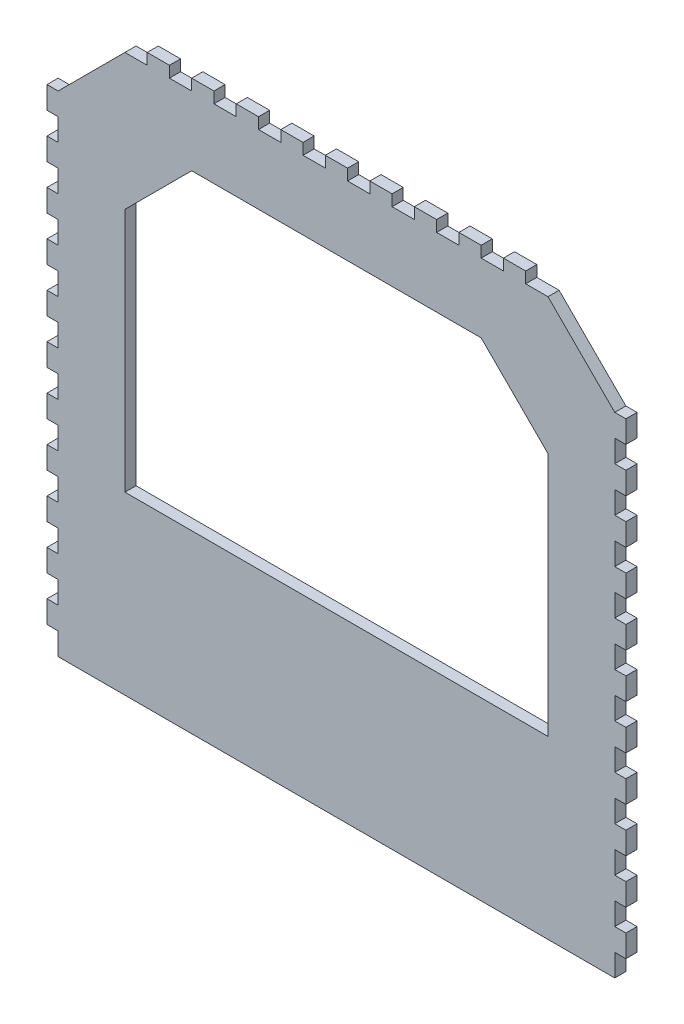
SolidWorks part; units mm, degrees
material "Buche"
ref_plane "Ebene vorne" through (0, 0, 0) normal (0, 0, 1) x (1, 0, 0)
ref_plane "Ebene oben" through (0, 0, 0) normal (0, 1, 0) x (1, 0, 0)
ref_plane "Ebene rechts" through (0, 0, 0) normal (1, 0, 0) x (0, 0, -1)
sketch "Skizze1" plane through (0, 0, 0) normal (0, 0, 1) x (1, 0, 0)
  line L0 (460.8962, 291.6639) -> (470.8962, 291.6639)
  line L1 (470.8962, 291.6639) -> (470.8962, 296.6639)
  line L2 (470.8962, 296.6639) -> (480.8962, 296.6639)
  line L3 (480.8962, 296.6639) -> (480.8962, 291.6639)
  line L4 (480.8962, 291.6639) -> (490.8962, 291.6639)
  line L5 (490.8962, 291.6639) -> (490.8962, 296.6639)
  line L6 (490.8962, 296.6639) -> (500.8962, 296.6639)
  line L7 (500.8962, 296.6639) -> (500.8962, 291.6639)
  line L8 (500.8962, 291.6639) -> (510.8962, 291.6639)
  line L9 (510.8962, 291.6639) -> (510.8962, 296.6639)
  line L10 (510.8962, 296.6639) -> (520.8962, 296.6639)
  line L11 (520.8962, 296.6639) -> (520.8962, 291.6639)
  line L12 (520.8962, 291.6639) -> (530.8962, 291.6639)
  line L13 (530.8962, 291.6639) -> (530.8962, 296.6639)
  line L14 (530.8962, 296.6639) -> (540.8962, 296.6639)
  line L15 (540.8962, 296.6639) -> (540.8962, 291.6639)
  line L16 (540.8962, 291.6639) -> (550.8962, 291.6639)
  line L17 (550.8962, 291.6639) -> (550.8962, 296.6639)
  line L18 (550.8962, 296.6639) -> (560.8962, 296.6639)
  line L19 (560.8962, 296.6639) -> (560.8962, 291.6639)
  line L20 (560.8962, 291.6639) -> (570.8962, 291.6639)
  line L21 (570.8962, 291.6639) -> (570.8962, 296.6639)
  line L22 (570.8962, 296.6639) -> (580.8962, 296.6639)
  line L23 (580.8962, 296.6639) -> (580.8962, 291.6639)
  line L24 (580.8962, 291.6639) -> (590.8962, 291.6639)
  line L25 (590.8962, 291.6639) -> (590.8962, 296.6639)
  line L26 (590.8962, 296.6639) -> (600.8962, 296.6639)
  line L27 (600.8962, 296.6639) -> (600.8962, 291.6639)
  line L28 (600.8962, 291.6639) -> (610.8962, 291.6639)
  line L29 (610.8962, 291.6639) -> (610.8962, 296.6639)
  line L30 (610.8962, 296.6639) -> (620.8962, 296.6639)
  line L31 (620.8962, 296.6639) -> (620.8962, 291.6639)
  line L32 (620.8962, 291.6639) -> (630.8962, 291.6639)
  line L33 (630.8962, 291.6639) -> (630.8962, 296.6639)
  line L34 (630.8962, 296.6639) -> (640.8962, 296.6639)
  line L35 (640.8962, 296.6639) -> (640.8962, 291.6639)
  line L36 (640.8962, 291.6639) -> (650.8962, 291.6639)
  line L197 (680.8962, 261.6639) -> (685.8962, 261.6639)
  line L198 (685.8962, 261.6639) -> (685.8962, 251.6639)
  line L199 (430.8962, 231.6639) -> (430.8962, 221.6639)
  line L200 (490.8962, 260.635) -> (620.8962, 260.635)
  line L201 (680.8962, 251.6639) -> (680.8962, 241.6639)
  line L202 (680.8962, 241.6639) -> (685.8962, 241.6639)
  line L203 (685.8962, 241.6639) -> (685.8962, 231.6639)
  line L204 (430.8962, 241.6639) -> (425.8962, 241.6639)
  line L205 (430.8962, 251.6639) -> (430.8962, 241.6639)
  line L206 (425.8962, 231.6639) -> (430.8962, 231.6639)
  line L207 (460.8962, 120.635) -> (460.8962, 230.635)
  line L208 (680.8962, 231.6639) -> (680.8962, 221.6639)
  line L209 (685.8962, 231.6639) -> (680.8962, 231.6639)
  line L210 (425.8962, 241.6639) -> (425.8962, 231.6639)
  line L211 (430.8962, 211.6639) -> (430.8962, 201.6639)
  line L212 (430.8962, 221.6639) -> (425.8962, 221.6639)
  line L213 (425.8962, 211.6639) -> (430.8962, 211.6639)
  line L214 (430.8962, 261.6639) -> (460.8962, 291.6639)
  line L215 (680.8962, 221.6639) -> (685.8962, 221.6639)
  line L216 (685.8962, 221.6639) -> (685.8962, 211.6639)
  line L217 (680.8962, 211.6639) -> (680.8962, 201.6639)
  line L218 (425.8962, 221.6639) -> (425.8962, 211.6639)
  line L219 (430.8962, 261.6639) -> (425.8962, 261.6639)
  line L220 (685.8962, 211.6639) -> (680.8962, 211.6639)
  line L221 (680.8962, 201.6639) -> (685.8962, 201.6639)
  line L222 (430.8962, 191.6639) -> (430.8962, 181.6639)
  line L223 (430.8962, 201.6639) -> (425.8962, 201.6639)
  line L224 (650.8962, 230.635) -> (620.8962, 260.635)
  line L225 (685.8962, 201.6639) -> (685.8962, 191.6639)
  line L226 (680.8962, 191.6639) -> (680.8962, 181.6639)
  line L227 (685.8962, 191.6639) -> (680.8962, 191.6639)
  line L228 (425.8962, 191.6639) -> (430.8962, 191.6639)
  line L229 (425.8962, 201.6639) -> (425.8962, 191.6639)
  line L230 (680.8962, 181.6639) -> (685.8962, 181.6639)
  line L231 (685.8962, 181.6639) -> (685.8962, 171.6639)
  line L232 (685.8962, 251.6639) -> (680.8962, 251.6639)
  line L233 (430.8962, 171.6639) -> (430.8962, 161.6639)
  line L234 (430.8962, 181.6639) -> (425.8962, 181.6639)
  line L235 (425.8962, 251.6639) -> (430.8962, 251.6639)
  line L236 (425.8962, 171.6639) -> (430.8962, 171.6639)
  line L237 (680.8962, 171.6639) -> (680.8962, 161.6639)
  line L238 (425.8962, 181.6639) -> (425.8962, 171.6639)
  line L239 (430.8962, 151.6639) -> (430.8962, 141.6639)
  line L240 (430.8962, 161.6639) -> (425.8962, 161.6639)
  line L241 (460.8962, 120.635) -> (650.8962, 120.635)
  line L242 (685.8962, 171.6639) -> (680.8962, 171.6639)
  line L243 (680.8962, 161.6639) -> (685.8962, 161.6639)
  line L244 (685.8962, 161.6639) -> (685.8962, 151.6639)
  line L245 (680.8962, 151.6639) -> (680.8962, 141.6639)
  line L246 (685.8962, 151.6639) -> (680.8962, 151.6639)
  line L247 (425.8962, 151.6639) -> (430.8962, 151.6639)
  line L248 (425.8962, 161.6639) -> (425.8962, 151.6639)
  line L249 (430.8962, 131.6639) -> (430.8962, 121.6639)
  line L250 (430.8962, 141.6639) -> (425.8962, 141.6639)
  line L251 (425.8962, 131.6639) -> (430.8962, 131.6639)
  line L252 (430.8962, 41.6639) -> (680.8962, 41.6639)
  line L253 (460.8962, 230.635) -> (490.8962, 260.635)
  line L254 (680.8962, 141.6639) -> (685.8962, 141.6639)
  line L255 (685.8962, 141.6639) -> (685.8962, 131.6639)
  line L256 (680.8962, 131.6639) -> (680.8962, 121.6639)
  line L257 (685.8962, 131.6639) -> (680.8962, 131.6639)
  line L258 (680.8962, 121.6639) -> (685.8962, 121.6639)
  line L259 (685.8962, 121.6639) -> (685.8962, 111.6639)
  line L260 (425.8962, 141.6639) -> (425.8962, 131.6639)
  line L261 (430.8962, 111.6639) -> (430.8962, 101.6639)
  line L262 (680.8962, 111.6639) -> (680.8962, 101.6639)
  line L263 (650.8962, 120.635) -> (650.8962, 230.635)
  line L264 (685.8962, 111.6639) -> (680.8962, 111.6639)
  line L265 (430.8962, 121.6639) -> (425.8962, 121.6639)
  line L266 (425.8962, 111.6639) -> (430.8962, 111.6639)
  line L267 (425.8962, 121.6639) -> (425.8962, 111.6639)
  line L268 (430.8962, 91.6639) -> (430.8962, 81.6639)
  line L269 (680.8962, 101.6639) -> (685.8962, 101.6639)
  line L270 (685.8962, 101.6639) -> (685.8962, 91.6639)
  line L271 (680.8962, 91.6639) -> (680.8962, 81.6639)
  line L272 (430.8962, 101.6639) -> (425.8962, 101.6639)
  line L273 (425.8962, 91.6639) -> (430.8962, 91.6639)
  line L274 (680.8962, 261.6639) -> (650.8962, 291.6639)
  line L275 (685.8962, 91.6639) -> (680.8962, 91.6639)
  line L276 (680.8962, 81.6639) -> (685.8962, 81.6639)
  line L277 (425.8962, 101.6639) -> (425.8962, 91.6639)
  line L278 (430.8962, 71.6639) -> (430.8962, 61.6639)
  line L279 (425.8962, 261.6639) -> (425.8962, 251.6639)
  line L280 (430.8962, 81.6639) -> (425.8962, 81.6639)
  line L281 (685.8962, 81.6639) -> (685.8962, 71.6639)
  line L282 (680.8962, 71.6639) -> (680.8962, 61.6639)
  line L283 (685.8962, 71.6639) -> (680.8962, 71.6639)
  line L284 (680.8962, 61.6639) -> (685.8962, 61.6639)
  line L285 (685.8962, 61.6639) -> (685.8962, 51.6639)
  line L286 (425.8962, 71.6639) -> (430.8962, 71.6639)
  line L287 (680.8962, 51.6639) -> (680.8962, 41.6639)
  line L288 (685.8962, 51.6639) -> (680.8962, 51.6639)
  line L289 (425.8962, 81.6639) -> (425.8962, 71.6639)
  line L290 (430.8962, 51.6639) -> (430.8962, 41.6639)
  line L291 (430.8962, 61.6639) -> (425.8962, 61.6639)
  line L292 (425.8962, 51.6639) -> (430.8962, 51.6639)
  line L293 (425.8962, 61.6639) -> (425.8962, 51.6639)
  dimension "D1" = 9
extrude "Aufsatz-Linear austragen1" add sketch "Skizze1" along normal blind 5
